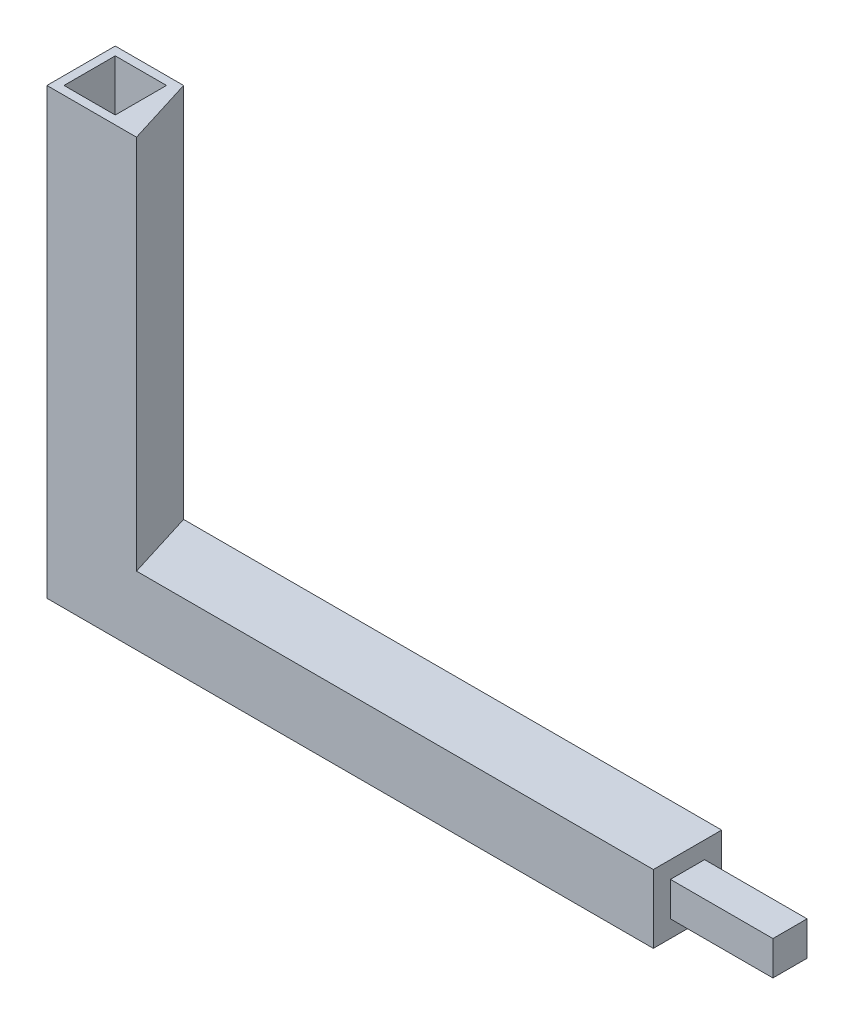
SolidWorks part; units mm, degrees
ref_plane "Plan de face" through (0, 0, 0) normal (0, 0, 1) x (1, 0, 0)
ref_plane "Plan de dessus" through (0, 0, 0) normal (0, 1, 0) x (1, 0, 0)
ref_plane "Plan de droite" through (0, 0, 0) normal (1, 0, 0) x (0, 0, -1)
sketch "Esquisse2" plane through (0, 0, 0) normal (0, 1, 0) x (1, 0, 0)
  line L0 (0, 0) -> (0, 20)
  line L1 (0, 20) -> (177.5, 20)
  line L2 (177.5, 20) -> (177.5, 0)
  line L3 (177.5, 0) -> (0, 0)
  dimension "D1" = 177.5
  dimension "D2" = 20
extrude "Boss.-Extru.1" add sketch "Esquisse2" along normal blind 20
sketch "Esquisse4" plane through (0, 20, 0) normal (0, 1, 0) x (1, 0, 0)
  line L0 (0, 20) -> (20, 20)
  line L1 (177.5, 20) -> (0, 20) construction
  line L2 (20, 20) -> (26.2293, 0)
  line L3 (0, 0) -> (177.5, 0) construction
  line L4 (26.2293, 0) -> (0, 0)
  line L5 (0, 0) -> (0, 20)
  dimension "D1" = 20
  dimension "D2" = 107.3
extrude "Boss.-Extru.3" add sketch "Esquisse4" along normal blind 110
sketch "Esquisse5" plane through (177.5, 0, 0) normal (1, 0, 0) x (0, 0, -1)
  line L0 (20, 20) -> (20, 0) construction
  line L1 (5, 15) -> (15, 15)
  line L2 (5, 15) -> (5, 5)
  line L3 (5, 5) -> (15, 5)
  line L4 (15, 15) -> (15, 5)
  line L5 (5, 15) -> (15, 5) construction
  line L6 (5, 5) -> (15, 15) construction
  line L7 (0, 0) -> (20, 0) construction
  point P0 (10, 10)
  dimension "D1" = 10
  dimension "D2" = 10
  dimension "D3" = 10
  dimension "D4" = 10
extrude "Boss.-Extru.4" add sketch "Esquisse5" along normal blind 30
hole_wizard "Dégagement M31" positions "Esquisse3D1" profile "Esquisse7" hole size "M3" standard "Ansi Metric"
sketch3d "Esquisse3D1"
  line L1 (177.5, 0, -20) -> (0, 0, -20) construction
  line L2 (0, 130, -20) -> (0, 0, -20) construction
  point P1 (10, 80, -20)
  dimension "D1" = 80
  dimension "D2" = 10
sketch "Esquisse7" plane through (10, 80, -20) normal (1, 0, 0) x (0, 1, 0)
  line L0 (0, 0) -> (0, 10.9614)
  line L1 (0, 10.9614) -> (1.6, 10)
  line L2 (1.6, 10) -> (1.6, 0)
  line L5 (1.6, 0) -> (0, 0)
  line L10 (0, 10.9614) -> (-1.6, 10) construction
  line L11 (0, -6.35) -> (0, 107.95) construction
  dimension "Diamètre du perçage" = 3.2
  dimension "Profondeur du perçage" = 10
  dimension "Angle de pointe" = 118
sketch "Esquisse8" plane through (0, 130, 0) normal (0, 1, 0) x (1, 0, 0)
  line L1 (17.5, 2.5) -> (2.5, 2.5)
  line L2 (17.5, 2.5) -> (17.5, 17.5)
  line L3 (17.5, 17.5) -> (2.5, 17.5)
  line L4 (2.5, 2.5) -> (2.5, 17.5)
  line L5 (17.5, 2.5) -> (2.5, 17.5) construction
  line L6 (17.5, 17.5) -> (2.5, 2.5) construction
  line L7 (0, 0) -> (26.2293, 0) construction
  line L8 (0, 20) -> (0, 0) construction
  point P0 (10, 10)
  dimension "D1" = 10
  dimension "D2" = 10
  dimension "D3" = 15
  dimension "D4" = 15
extrude "Enlèv. mat.-Extru.1" cut sketch "Esquisse8" against normal blind 60
